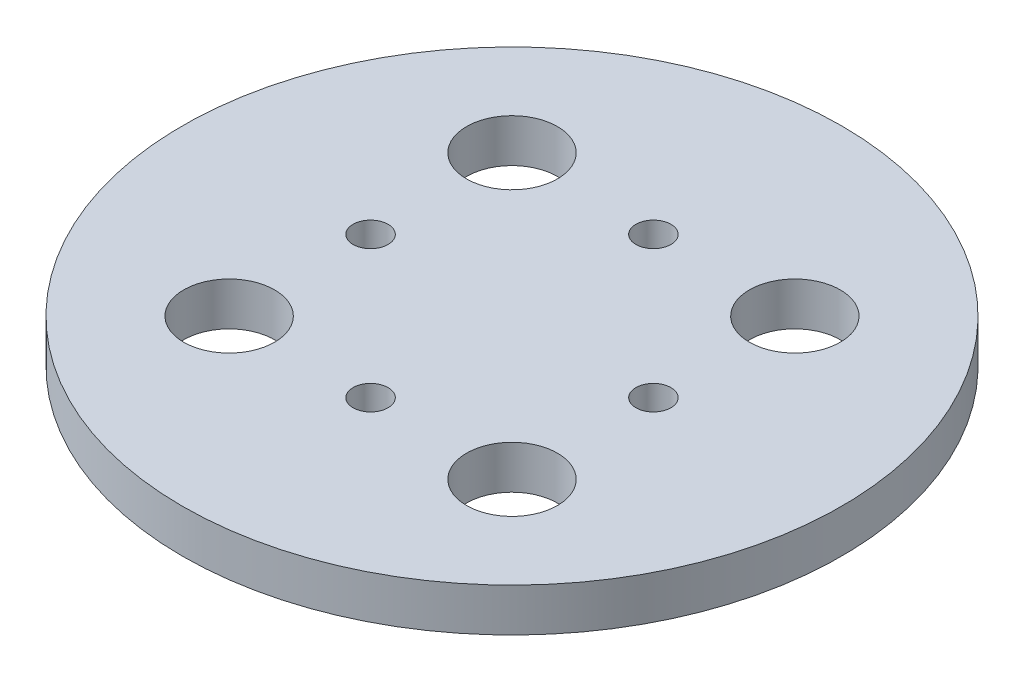
SolidWorks part; units mm, degrees
material "polylactic acid(PLA)"
ref_plane "Front Plane" through (0, 0, 0) normal (0, 0, 1) x (1, 0, 0)
ref_plane "Top Plane" through (0, 0, 0) normal (0, 1, 0) x (1, 0, 0)
ref_plane "Right Plane" through (0, 0, 0) normal (1, 0, 0) x (0, 0, -1)
sketch "Sketch2" plane through (0, 0, 0) normal (0, 1, 0) x (1, 0, 0)
  line L1 (-50, 50) -> (50, 50) construction
  line L2 (-50, 50) -> (-50, -50) construction
  line L3 (-50, -50) -> (50, -50) construction
  line L4 (50, 50) -> (50, -50) construction
  circle A0 centre (-32.7, 32.7) radius 10.5
  circle A1 centre (32.7, 32.7) radius 10.5
  circle A2 centre (32.7, -32.7) radius 10.5
  circle A3 centre (-32.7, -32.7) radius 10.5
  circle A4 centre (-32.7, 32.7) radius 17.3 construction
  circle A5 centre (-32.7, -32.7) radius 17.3 construction
  circle A6 centre (32.7, 32.7) radius 17.3 construction
  circle A7 centre (0, 32.7) radius 4.05
  circle A8 centre (0, 32.7) radius 7.5 construction
  circle A9 centre (32.7, 0) radius 4.05
  circle A10 centre (0, -32.7) radius 4.05
  circle A11 centre (-32.7, 0) radius 4.05
  circle A12 centre (0, 0) radius 76.2
  point P14 (0, 0)
  point P21 (0, 50)
  point P22 (0, 0)
  point P29 (0, 0)
  point P30 (50, 0)
  point P31 (-28.5496, 32.7)
  dimension "D1" = 21
  dimension "D2" = 34.6
  dimension "D4" = 8.1
  dimension "D5" = 15
  dimension "D7" = 152.4
  dimension "D9" = 100
  dimension "D3" = 4
  dimension "D6" = 4
extrude "Boss-Extrude2" add sketch "Sketch2" along normal blind 10
